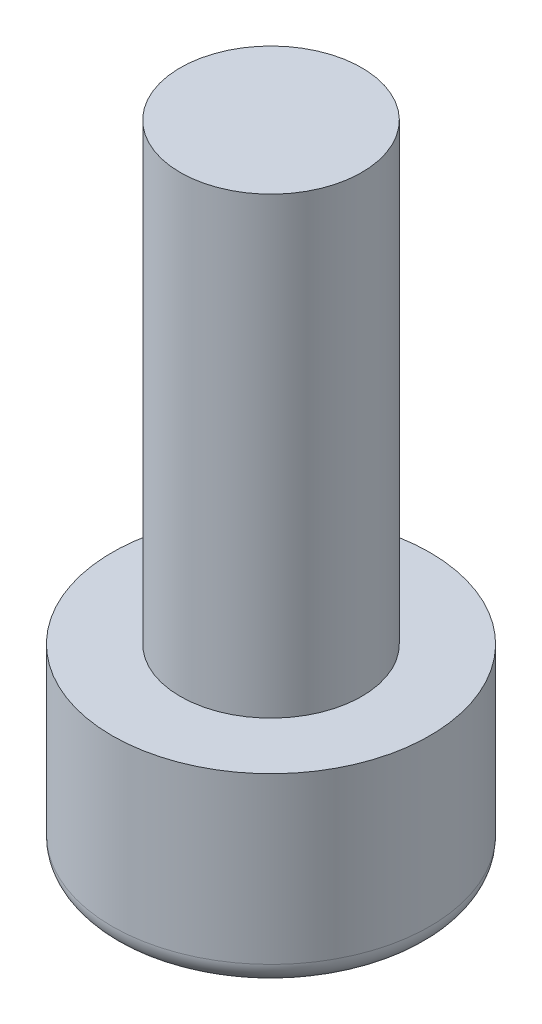
SolidWorks part; units mm, degrees
ref_plane "前视基准面" through (0, 0, 0) normal (0, 0, 1) x (1, 0, 0)
ref_plane "上视基准面" through (0, 0, 0) normal (0, 1, 0) x (1, 0, 0)
ref_plane "右视基准面" through (0, 0, 0) normal (1, 0, 0) x (0, 0, -1)
sketch "草图1" plane through (0, 0, 0) normal (0, 1, 0) x (1, 0, 0)
  circle A0 centre (0, 0) radius 3.5
  dimension "D1" = 7
extrude "凸台-拉伸1" add sketch "草图1" along normal blind 4.14
sketch "草图2" plane through (0, 4.14, 0) normal (0, 1, 0) x (1, 0, 0)
  circle A0 centre (0, 0) radius 2
  dimension "D1" = 4
extrude "凸台-拉伸2" add sketch "草图2" along normal blind 10
cosmetic thread "装饰螺纹线1" parameters "D2"=3.242
fillet "圆角1" radius 0.5 1 edges at (0, 0, 3.5)
sketch "草图3" plane through (0, 0, 0) normal (0, -1, 0) x (1, 0, 0)
  line L1 (1.6983, 2.0561) -> (-0.9315, 2.4988)
  line L2 (-0.9315, 2.4988) -> (-2.6298, 0.4427)
  line L3 (-2.6298, 0.4427) -> (-1.6983, -2.0561)
  line L4 (-1.6983, -2.0561) -> (0.9315, -2.4988)
  line L5 (0.9315, -2.4988) -> (2.6298, -0.4427)
  line L6 (2.6298, -0.4427) -> (1.6983, 2.0561)
  circle A0 centre (0, 0) radius 2.3095 construction
extrude "切除-拉伸1" cut sketch "草图3" against normal blind 2
